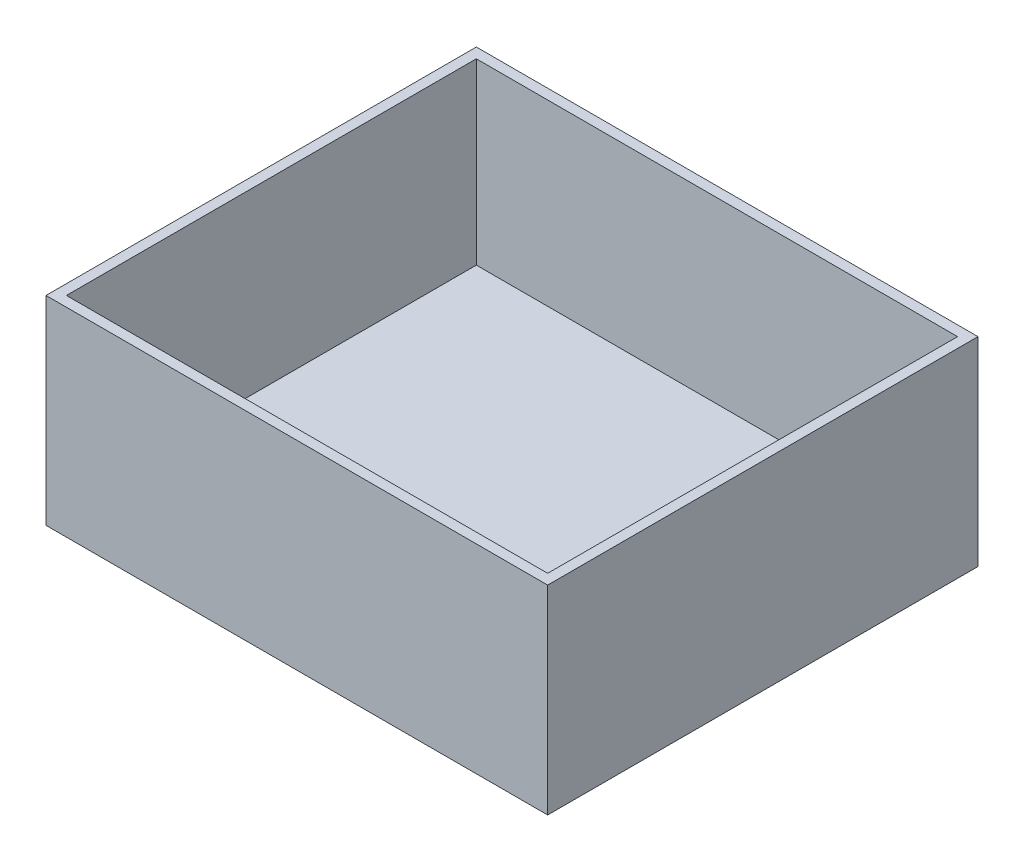
SolidWorks part; units mm, degrees
material "ABS"
ref_plane "Front Plane" through (0, 0, 0) normal (0, 0, 1) x (1, 0, 0)
ref_plane "Top Plane" through (0, 0, 0) normal (0, 1, 0) x (1, 0, 0)
ref_plane "Right Plane" through (0, 0, 0) normal (1, 0, 0) x (0, 0, -1)
sketch "Sketch1" plane through (0, 0, 0) normal (0, 1, 0) x (1, 0, 0)
  line L1 (-49.13, 42.145) -> (49.13, 42.145)
  line L2 (-49.13, 42.145) -> (-49.13, -42.145)
  line L3 (-49.13, -42.145) -> (49.13, -42.145)
  line L4 (49.13, 42.145) -> (49.13, -42.145)
  line L5 (-49.13, 42.145) -> (49.13, -42.145) construction
  line L6 (-49.13, -42.145) -> (49.13, 42.145) construction
  point P0 (0, 0)
  dimension "D1" = 84.29
  dimension "D2" = 98.26
extrude "Boss-Extrude1" add sketch "Sketch1" along normal blind 39
sketch "Sketch2" plane through (0, 39, 0) normal (0, 1, 0) x (1, 0, 0)
  line L1 (-47.13, 40.145) -> (47.13, 40.145)
  line L2 (-47.13, 40.145) -> (-47.13, -40.145)
  line L3 (-47.13, -40.145) -> (47.13, -40.145)
  line L4 (47.13, 40.145) -> (47.13, -40.145)
  line L5 (-47.13, 40.145) -> (47.13, -40.145) construction
  line L6 (-47.13, -40.145) -> (47.13, 40.145) construction
  point P0 (0, 0)
  dimension "D1" = 80.29
  dimension "D2" = 94.26
extrude "Cut-Extrude1" cut sketch "Sketch2" against normal blind 35
